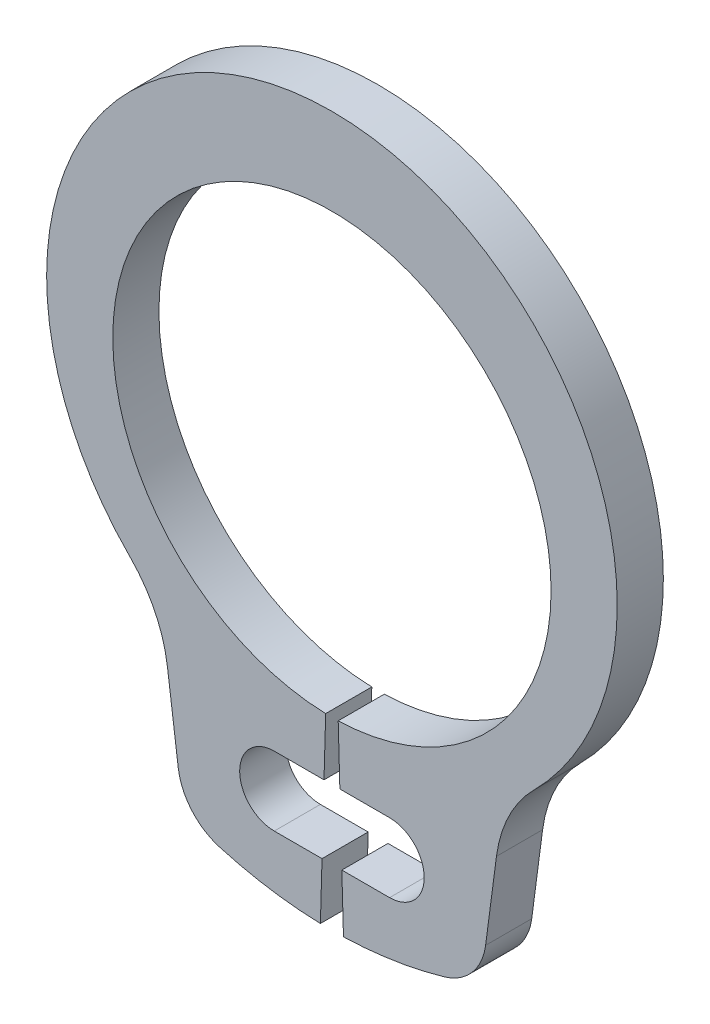
SolidWorks part; units mm, degrees
ref_plane "Plane1" through (0, 0, 0) normal (0, 0, 1) x (1, 0, 0)
ref_plane "Plane2" through (0, 0, 0) normal (0, 1, 0) x (1, 0, 0)
ref_plane "Plane3" through (0, 0, 0) normal (1, 0, 0) x (0, 0, -1)
sketch "Clipboard" plane through (0, 0, 0) normal (0, 0, 1) x (1, 0, 0)
  line L0 (0, 0) -> (1.5, 0)
  line L1 (0, 0) -> (0, 0.9)
  line L2 (0, 0) -> (0, -3.2)
  circle A0 centre (0, 0) radius 0.6
  circle A1 centre (0, 0) radius 4
  dimension "HoleDia" = 1.2
  dimension "ShaftDia" = 8
  dimension "LargeSection" = 1.5
  dimension "SmallSection" = 0.9
  dimension "LugSection" = 3.2
sketch "BodySke" plane through (0, 0, 0) normal (0, 0, 1) x (1, 0, 0)
  line L0 (-1.5431, 0) -> (1.5431, 0) construction
  line L1 (0, 0) -> (0, 5.3) construction
  line L2 (0.1086, -3.7984) -> (0.2, -6.9971)
  line L3 (-0.1086, -3.7984) -> (-0.2, -6.9971)
  line L4 (0, 0) -> (5.1312, -4.7614) construction
  line L5 (0, 0) -> (-5.1312, -4.7614) construction
  line L7 (2.853, -4.4615) -> (2.6646, -5.8925)
  line L8 (-2.853, -4.4615) -> (-2.6646, -5.8925)
  circle A0 centre (0, 0) radius 3.8 construction
  arc A1 (0.1086, -3.7984) -> (-0.1086, -3.7984) centre (0, 0) ccw
  arc A2 (3.4452, -3.1969) -> (-3.4452, -3.1969) centre (0, 0.3531) ccw construction
  arc A3 (0.2, -6.9971) -> (1.952, -6.7223) centre (0, 0) ccw
  arc A4 (3.5037, -3.1392) -> (2.853, -4.4615) centre (5.1312, -4.7614) ccw
  arc A5 (-2.853, -4.4615) -> (-3.5037, -3.1392) centre (-5.1312, -4.7614) ccw
  arc A6 (-1.952, -6.7223) -> (-0.2, -6.9971) centre (0, 0) ccw
  arc A7 (3.5037, -3.1392) -> (-3.5037, -3.1392) centre (0, 0.3531) ccw
  arc A8 (-2.8186, -4.7229) -> (2.8186, -4.7229) centre (0, 0) ccw construction
  circle A9 centre (1, -5.4083) radius 0.6
  circle A10 centre (-1, -5.4083) radius 0.6
  arc A11 (2.6646, -5.8925) -> (1.952, -6.7223) centre (1.6731, -5.762) cw
  arc A12 (-2.6646, -5.8925) -> (-1.952, -6.7223) centre (-1.6731, -5.762) ccw
  point P28 (2.5839, -6.5057)
  point P31 (-2.5839, -6.5057)
  dimension "GrooveDia" = 7.6
  dimension "D3" = 1
  dimension "LugRad" = 7
  dimension "HoleOffsetRad" = 5.5
  dimension "HoleDia" = 1.2
  dimension "D2" = 15
  dimension "LargeRad" = 5.3
  dimension "SmallRad" = 4.7
  dimension "Gap" = 0.4
  dimension "SmallAngle" = 94.281
  dimension "HoleSpacing" = 2
extrude "Body" add sketch "BodySke" against normal blind 0.8
sketch "NotSke" plane through (0, 0, 0) normal (0, 0, 1) x (1, 0, 0)
  line L0 (1, -4.8083) -> (1, -6.0083)
  line L1 (1, -6.0083) -> (-1, -6.0083)
  line L2 (-1, -6.0083) -> (-1, -4.8083)
  line L3 (-1, -4.8083) -> (1, -4.8083)
  circle A0 centre (1, -5.4083) radius 0.6 construction
  circle A1 centre (-1, -5.4083) radius 0.6 construction
extrude "Notch" cut sketch "NotSke" against normal through all
sketch "UnlSke" plane through (0, 0, 0) normal (0, 0, 1) x (1, 0, 0)
  line L0 (1.952, -3.2603) -> (1.952, -6.7223)
  line L1 (-1.952, -3.2603) -> (-1.952, -6.7223)
  arc A0 (1.952, -3.2603) -> (-1.952, -3.2603) centre (0, 0) ccw
  arc A1 (1.952, -6.7223) -> (-1.952, -6.7223) centre (0, 0) ccw
  arc A4 (-1.952, -6.7223) -> (-0.2, -6.9971) centre (0, 0) ccw construction
  arc A5 (0.1086, -3.7984) -> (-0.1086, -3.7984) centre (0, 0) ccw construction
extrude "Unlug" [suppressed] add sketch "UnlSke" against normal through all
equation "' \"ShaftDia@Clipboard\" = 3"
equation "' \"Thickness@Body\" = 0.4"
equation "' \"GrooveDia@BodySke\" = 2.8"
equation "' \"LugSection@Clipboard\" = 1.9"
equation "' \"LargeSection@Clipboard\" = 0.8"
equation "' \"HoleDia@Clipboard\" = 0.8"
equation "' \"ShaftDia@Clipboard\" = 9"
equation "' \"Thickness@Body\" = 1"
equation "' \"GrooveDia@BodySke\" = 8.6"
equation "' \"LugSection@Clipboard\" = 3.3"
equation "' \"LargeSection@Clipboard\" = 1.7"
equation "' \"HoleDia@Clipboard\" = 1.2"
equation "\"SmallSection@Clipboard\" =  \"LargeSection@Clipboard\" * 0.6"
equation "\"Gap@BodySke\" =  \"Thickness@Body\" / 2"
equation "\"LargeRad@BodySke\" =  \"GrooveDia@BodySke\" / 2 +  \"LargeSection@Clipboard\""
equation "\"SmallRad@BodySke\" =  \"GrooveDia@BodySke\" / 2 +  \"SmallSection@Clipboard\""
equation "\"LugRad@BodySke\" = \"GrooveDia@BodySke\" / 2 + \"LugSection@Clipboard\""
equation "\"HoleOffsetRad@BodySke\" = (  \"ShaftDia@Clipboard\" / 2 + \"LugRad@BodySke\" ) / 2"
equation "\"HoleSpacing@BodySke\" = \"Gap@BodySke\"  * 2 +  \"HoleDia@Clipboard\""
equation "\"HoleDia@BodySke\" =  \"HoleDia@Clipboard\""
equation "\"SmallAngle@BodySke\" = atn(\"HoleSpacing@BodySke\" / 2 / sqr(\"HoleOffsetRad@BodySke\"  * \"HoleOffsetRad@BodySke\" - (\"HoleSpacing@BodySke\" / 2) * (\"HoleSpacing@BodySke\" / 2) ))  * 9 * ( 180 / 3.141593)"
